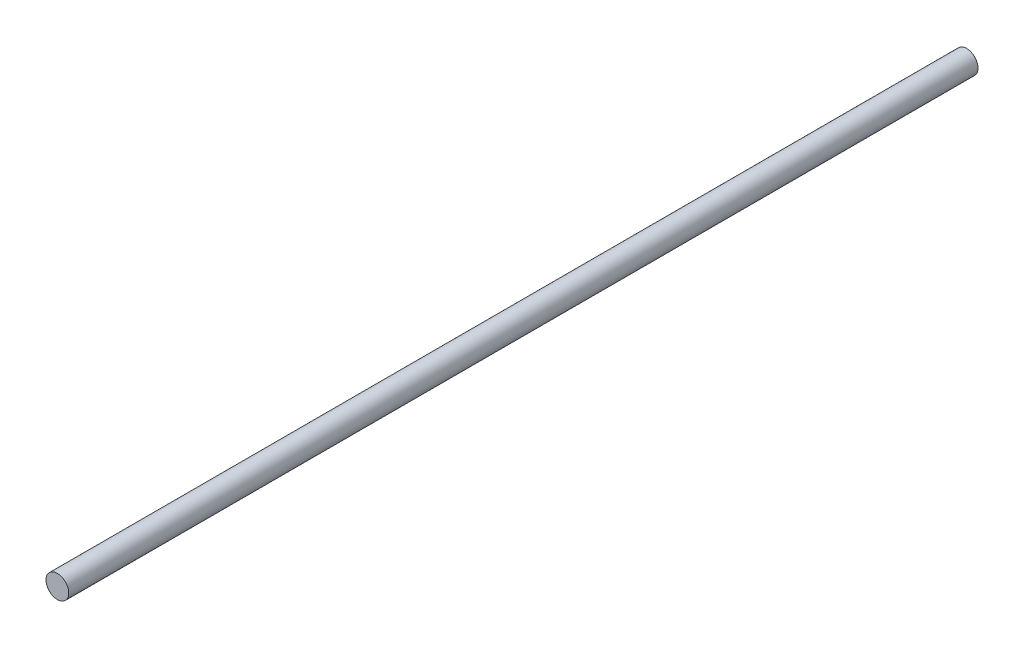
SolidWorks part; units mm, degrees
ref_plane "Front Plane" through (0, 0, 0) normal (0, 0, 1) x (1, 0, 0)
ref_plane "Top Plane" through (0, 0, 0) normal (0, 1, 0) x (1, 0, 0)
ref_plane "Right Plane" through (0, 0, 0) normal (1, 0, 0) x (0, 0, -1)
sketch "Sketch1" plane through (0, 0, 0) normal (0, 0, 1) x (1, 0, 0)
  circle A0 centre (0, 0) radius 3.81
  dimension "D1" = 7.62
extrude "Boss-Extrude1" add sketch "Sketch1" along normal blind 304.8 contours A0
